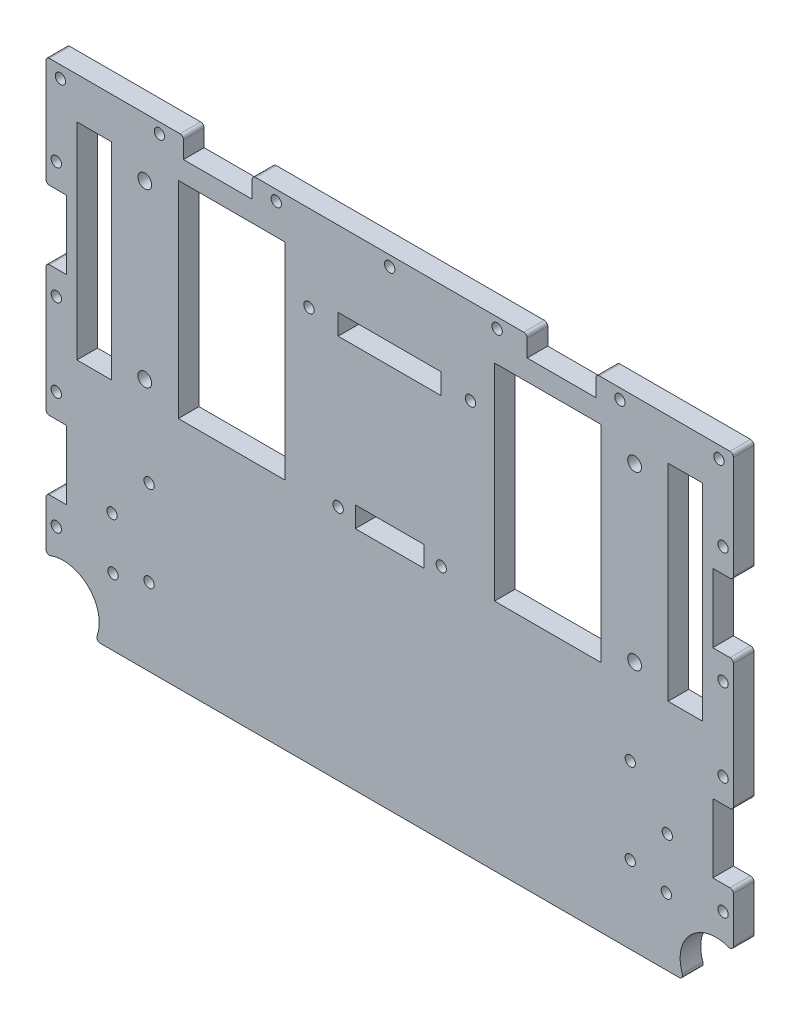
SolidWorks part; units mm, degrees
ref_plane "Plan de face" through (0, 0, 0) normal (0, 0, 1) x (1, 0, 0)
ref_plane "Plan de dessus" through (0, 0, 0) normal (0, 1, 0) x (1, 0, 0)
ref_plane "Plan de droite" through (0, 0, 0) normal (1, 0, 0) x (0, 0, -1)
sketch "Esquisse1" plane through (0, 0, 0) normal (0, 0, 1) x (1, 0, 0)
  line L1 (0, 0) -> (200, 0)
  line L2 (0, 0) -> (0, -140)
  line L3 (0, -140) -> (200, -140)
  line L4 (200, 0) -> (200, -140)
  dimension "D1" = 200
  dimension "D2" = 140
extrude "Boss.-Extru.1" add sketch "Esquisse1" along normal blind 6 contours L1 L4 L3 L2
sketch "Esquisse8" plane through (0, 0, 0) normal (0, 0, -1) x (-1, 0, 0)
  line L1 (-161.5, -12) -> (-130.5, -12)
  line L2 (-100, 0) -> (-100, -140) construction
  line L3 (0, 0) -> (-200, 0) construction
  line L4 (0, -140) -> (-200, -140) construction
  line L5 (-161.5, -12) -> (-161.5, -72)
  line L6 (-161.5, -72) -> (-130.5, -72)
  line L7 (-130.5, -12) -> (-130.5, -72)
  line L8 (-191, -12) -> (-181, -12)
  line L9 (-200, 0) -> (-200, -140) construction
  line L10 (-181, -12) -> (-181, -72)
  line L11 (-181, -72) -> (-191, -72)
  line L12 (-9, -12) -> (-19, -12)
  line L13 (-19, -72) -> (-9, -72)
  line L14 (-19, -12) -> (-19, -72)
  line L15 (-38.5, -12) -> (-69.5, -12)
  line L16 (-69.5, -12) -> (-69.5, -72)
  line L17 (-38.5, -72) -> (-69.5, -72)
  line L18 (-38.5, -12) -> (-38.5, -72)
  line L19 (-191, -12) -> (-191, -72)
  line L20 (-9, -12) -> (-9, -72)
  line M5 (0, -140) -> (0, 0)
  line M7 (-200, 0) -> (-200, -140)
  dimension "D1" = 30.5
  dimension "D2" = 31
  dimension "D3" = 12
  dimension "D4" = 10
  dimension "D5" = 60
  dimension "D6" = 60
  dimension "D7" = 9
extrude "Enlèv. mat.-Extru.2" cut sketch "Esquisse8" against normal blind 6 contours L11 L10 L8 M7 | L7 L1 L5 L6 | L18 L15 L16 L17 | L12 L14 L13 M5
sketch "Esquisse9" plane through (0, 0, 0) normal (0, 0, -1) x (-1, 0, 0)
  line L0 (0, 0) -> (-200, 0) construction
  line L5 (0, 0) -> (-200, 0) construction
  line L8 (-100, 0) -> (-100, -140) construction
  line L11 (-160, -6) -> (-140, -6)
  line L12 (-160, -6) -> (-160, 0)
  line L13 (-160, 0) -> (-140, 0)
  line L14 (-140, 0) -> (-140, -6)
  line L15 (-60, 0) -> (-60, -6)
  line L16 (-40, 0) -> (-60, 0)
  line L17 (-40, -6) -> (-60, -6)
  line L18 (-40, -6) -> (-40, 0)
  dimension "D1" = 20
  dimension "D2" = 40
  dimension "D3" = 6
extrude "Enlèv. mat.-Extru.3" cut sketch "Esquisse9" against normal blind 6
sketch "Esquisse10" plane through (0, 0, 0) normal (0, 0, -1) x (-1, 0, 0)
  line L2 (-194, -110) -> (-200, -110)
  line L3 (-200, 0) -> (-200, -140) construction
  line L4 (-194, -110) -> (-194, -90)
  line L5 (-194, -90) -> (-200, -90)
  line L6 (-200, -90) -> (-200, -110)
  line L7 (-100, -140) -> (-100, 0) construction
  line L8 (0, -140) -> (-200, -140) construction
  line L10 (-6, -90) -> (0, -90)
  line L11 (-6, -110) -> (-6, -90)
  line L12 (0, -90) -> (0, -110)
  line L13 (-6, -110) -> (0, -110)
  line L14 (0, -140) -> (-200, -140) construction
  dimension "D1" = 30
  dimension "D2" = 20
  dimension "D3" = 6
extrude "Enlèv. mat.-Extru.4" cut sketch "Esquisse10" against normal blind 6
sketch "Esquisse14" plane through (0, 0, 6) normal (0, 0, 1) x (1, 0, 0)
  line L0 (115, -28) -> (115, -22)
  line L1 (115, -22) -> (85, -22)
  line L2 (85, -22) -> (85, -28)
  line L3 (85, -28) -> (115, -28)
  line L4 (60, 0) -> (140, 0) construction
  line L5 (100, 0) -> (100, -140.1204) construction
  line L6 (69.5, -42) -> (130.5, -42) construction
  line L7 (69.5, -12) -> (69.5, -72) construction
  line L8 (130.5, -12) -> (130.5, -72) construction
  dimension "D1" = 30
  dimension "D2" = 15
  dimension "D3" = 14
  dimension "D4" = 6
extrude "Enlèv. mat.-Extru.7" cut sketch "Esquisse14" against normal blind 6
sketch "Esquisse15" plane through (0, 0, 6) normal (0, 0, 1) x (1, 0, 0)
  line L2 (200, -110) -> (200, -140) construction
  line L4 (100, -140) -> (100, 0) construction
  line L5 (0, -140) -> (200, -140) construction
  circle A0 centre (195, -135) radius 10.5
  circle A2 centre (5, -135) radius 10.5
  point P2 (200, -125)
  dimension "D1" = 21
  dimension "D4" = 21
  dimension "D2" = 5
  dimension "D3" = 5
extrude "Enlèv. mat.-Extru.8" cut sketch "Esquisse15" against normal blind 6
sketch "Esquisse19" plane through (0, 0, 0) normal (0, 0, -1) x (-1, 0, 0)
  line L0 (-100, 0) -> (-100, -83.7184) construction
  line L2 (-60, 0) -> (-140, 0) construction
  line L3 (-19, -12) -> (-19, -72) construction
  line L4 (-9, -12) -> (-19, -12) construction
  line L5 (-19, -72) -> (-9, -72) construction
  circle A0 centre (-28.75, -67) radius 2
  circle A1 centre (-28.75, -17) radius 2
  circle A3 centre (-171.25, -17) radius 2
  circle A4 centre (-171.25, -67) radius 2
  point P8 (-14, -72)
  dimension "D3" = 4
  dimension "D5" = 4
  dimension "D1" = 5
  dimension "D2" = 9.75
  dimension "D4" = 5
  dimension "D6" = 9.75
extrude "Enlèv. mat.-Extru.11" cut sketch "Esquisse19" against normal through all
sketch "Esquisse20" plane through (0, 0, 6) normal (0, 0, 1) x (1, 0, 0)
  line L0 (100, -140) -> (100, -14.1) construction
  line L1 (14.2331, -140) -> (185.7669, -140) construction
  line L2 (12.4246, -127.5754) -> (41.2146, -98.7854) construction
  line L3 (85, -22) -> (85, -28) construction
  line L4 (0, -110) -> (0, -125.7669) construction
  line L5 (115, -28) -> (115, -22) construction
  line L6 (115, -22) -> (85, -22) construction
  line L7 (0, 0) -> (0, -90) construction
  line L8 (6, -90) -> (6, -110) construction
  line L9 (14.2331, -140) -> (185.7669, -140) construction
  circle A0 centre (19.4957, -120.5043) radius 1.5
  circle A1 centre (19.2128, -105.507) radius 1.5
  circle A2 centre (180.7872, -105.507) radius 1.5
  circle A3 centre (30, -117.5) radius 1.5
  circle A4 centre (30, -92.5) radius 1.5
  circle A5 centre (180.5043, -120.5043) radius 1.5
  circle A6 centre (170, -92.5) radius 1.5
  circle A7 centre (170, -117.5) radius 1.5
  circle A8 centre (76.5, -25) radius 1.5
  circle A9 centre (123.5, -25) radius 1.5
  arc A10 (14.2331, -140) -> (0, -125.7669) centre (5, -135) ccw construction
  point P32 (115, -25)
  dimension "D2" = 3
  dimension "D5" = 19.4957
  dimension "D6" = 19.2128
  dimension "D9" = 3
  dimension "D10" = 3
  dimension "D3" = 3
  dimension "D7" = 15
  dimension "D8" = 3
  dimension "D15" = 3
  dimension "D16" = 24
  dimension "D17" = 24
  dimension "D18" = 22.5
  dimension "D19" = 25
  dimension "D4" = 10
  dimension "D11" = 8.5
  dimension "D12" = 8.5
  dimension "D13" = 3
  dimension "D14" = 3
extrude "Enlèv. mat.-Extru.12" cut sketch "Esquisse20" against normal through all
sketch "Esquisse21" plane through (0, 0, 0) normal (0, 0, -1) x (-1, 0, 0)
  line L0 (-100, 0) -> (-100, -140) construction
  line L1 (-60, 0) -> (-140, 0) construction
  line L9 (-85, -28) -> (-115, -28) construction
  line L12 (-110, -68) -> (-90, -68)
  line L13 (-110, -68) -> (-110, -74)
  line L18 (-110, -74) -> (-90, -74)
  line L19 (-90, -68) -> (-90, -74)
  circle A6 centre (-85, -71) radius 1.5
  circle A7 centre (-115, -71) radius 1.5
  dimension "D22" = 3
  dimension "D23" = 3
  dimension "D26" = 3
  dimension "D27" = 3
  dimension "D18" = 6
  dimension "D19" = 10
  dimension "D20" = 20
  dimension "D21" = 40
  dimension "D24" = 5
  dimension "D25" = 5
extrude "Enlèv. mat.-Extru.13" cut sketch "Esquisse21" against normal blind 10
sketch "Esquisse23" plane through (0, 0, 0) normal (0, 0, -1) x (-1, 0, 0)
  line L0 (-100, 0) -> (-100, -140) construction
  line L1 (-60, 0) -> (-140, 0) construction
  line L4 (-205.3, -135) -> (-205.3, 6.6228) construction
  line L5 (-160, 0) -> (-200, 0) construction
  line L7 (-14.2331, -140) -> (-185.7669, -140) construction
  circle A0 centre (-4.2, -3.5) radius 1.5
  circle A2 centre (-195, -135) radius 10.3 construction
  circle A3 centre (-195.8, -3.5) radius 1.5
  dimension "D1" = 3
  dimension "D4" = 9.5
  dimension "D2" = 20.6
  dimension "D3" = 3
  dimension "D7" = 3.5
extrude "Enlèv. mat.-Extru.15" cut sketch "Esquisse23" against normal blind 6
sketch "Esquisse16" plane through (0, 0, 0) normal (0, 0, -1) x (-1, 0, 0)
  line L0 (-60, 0) -> (-140, 0) construction
  line L1 (0, -90) -> (-6, -90) construction
  line L2 (0, 0) -> (0, -90) construction
  line L6 (-200, 0) -> (-200, -90) construction
  line L7 (-194, -90) -> (-200, -90) construction
  line L8 (0, -110) -> (0, -125.7669) construction
  line L9 (-6, -110) -> (0, -110) construction
  line L10 (-100, -140) -> (-100, 0) construction
  line L11 (-14.2331, -140) -> (-185.7669, -140) construction
  circle A0 centre (-3, -83) radius 1.5
  circle A1 centre (-197, -117) radius 1.5
  circle A3 centre (-197, -83) radius 1.5
  circle A4 centre (-3, -117) radius 1.5
  dimension "D2" = 3
  dimension "D4" = 3
  dimension "D12" = 7
  dimension "D13" = 3
  dimension "D6" = 7
  dimension "D7" = 3
  dimension "D11" = 3
  dimension "D14" = 3
  dimension "D15" = 7
extrude "Enlèv. mat.-Extru.9" cut sketch "Esquisse16" against normal blind 6
sketch "Esquisse28" plane through (0, 0, 6) normal (0, 0, 1) x (1, 0, 0)
  line L0 (0, 0) -> (0, -90) construction
  line L1 (0, -32) -> (6, -32)
  line L2 (0, -32) -> (0, -52)
  line L3 (0, -52) -> (6, -52)
  line L4 (6, -32) -> (6, -52)
  line L5 (9, -12) -> (19, -12) construction
  line L6 (60, 0) -> (140, 0) construction
  line L9 (100, 0) -> (100, -140) construction
  line L11 (14.2331, -140) -> (185.7669, -140) construction
  line L12 (194, -32) -> (194, -52)
  line L13 (200, -52) -> (194, -52)
  line L14 (200, -32) -> (200, -52)
  line L15 (200, -32) -> (194, -32)
  dimension "D1" = 20
  dimension "D2" = 20
  dimension "D3" = 6
extrude "Enlèv. mat.-Extru.17" cut sketch "Esquisse28" against normal through all
sketch "Esquisse29" plane through (0, 0, 0) normal (0, 0, -1) x (-1, 0, 0)
  line L0 (-200, 0) -> (-200, -32) construction
  line L1 (-60, 0) -> (-140, 0) construction
  line L2 (-200, -32) -> (-194, -32) construction
  line L3 (-194, -52) -> (-200, -52) construction
  line L4 (-200, -52) -> (-200, -90) construction
  line L5 (-100, 0) -> (-100, -140) construction
  line L7 (-14.2331, -140) -> (-185.7669, -140) construction
  circle A2 centre (-197, -25) radius 1.5
  circle A3 centre (-197, -59) radius 1.5
  circle A4 centre (-3, -59) radius 1.5
  circle A5 centre (-3, -25) radius 1.5
  dimension "D7" = 3
  dimension "D8" = 3
  dimension "D9" = 7
  dimension "D10" = 7
  dimension "D11" = 3
  dimension "D12" = 3
extrude "Enlèv. mat.-Extru.18" cut sketch "Esquisse29" against normal through all
sketch "Esquisse35" plane through (0, 0, 0) normal (0, 0, -1) x (-1, 0, 0)
  line L0 (-160, 0) -> (-160, -6) construction
  line L1 (-160, 0) -> (-200, 0) construction
  line L2 (-60, 0) -> (-140, 0) construction
  line L3 (-140, -6) -> (-140, 0) construction
  line L4 (-60, 0) -> (-60, -6) construction
  line L5 (0, 0) -> (-40, 0) construction
  line L6 (-40, -6) -> (-40, 0) construction
  circle A0 centre (-167, -3) radius 1.5
  circle A1 centre (-131.2604, -3) radius 1.5
  circle A2 centre (-100, -3) radius 1.5
  circle A3 centre (-67, -3) radius 1.5
  circle A4 centre (-33, -3) radius 1.5
  point P16 (-140, -3)
  point P19 (-60, -3)
  point P24 (-40, -3)
  dimension "D1" = 3
  dimension "D2" = 3
  dimension "D3" = 3
  dimension "D4" = 3
  dimension "D5" = 3
  dimension "D6" = 7
  dimension "D7" = 3
  dimension "D8" = 3
  dimension "D9" = 8.7396
  dimension "D10" = 40
  dimension "D11" = 7
  dimension "D12" = 3
  dimension "D14" = 3
  dimension "D15" = 7
  dimension "D13" = 3
extrude "Enlèv. mat.-Extru.21" cut sketch "Esquisse35" against normal blind 6
fillet "Congé1" radius 1 18 edges at (14.2331, -140, 3) (0, -125.7669, 3) (0, -110, 3) (0, -90, 3) (0, -52, 3) (0, -32, 3) (0, 0, 3) (40, 0, 3) (60, 0, 3) (140, 0, 3) (160, 0, 3) (200, 0, 3) (200, -32, 3) (200, -52, 3) (200, -110, 3) (200, -90, 3) (185.7669, -140, 3) (200, -125.7669, 3)
